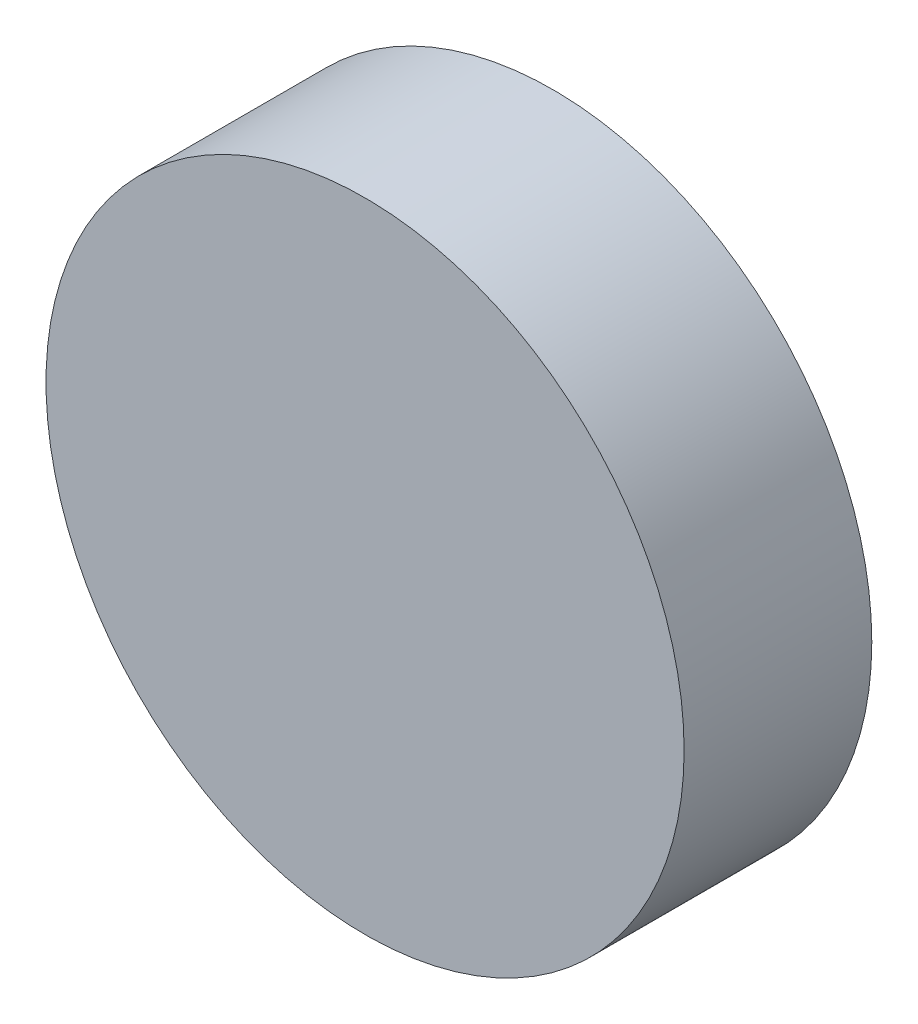
SolidWorks part; units mm, degrees
ref_plane "Front Plane" through (0, 0, 0) normal (0, 0, 1) x (1, 0, 0)
ref_plane "Top Plane" through (0, 0, 0) normal (0, 1, 0) x (1, 0, 0)
ref_plane "Right Plane" through (0, 0, 0) normal (1, 0, 0) x (0, 0, -1)
sketch "Sketch1" plane through (0, 0, 0) normal (0, 0, 1) x (1, 0, 0)
  circle A0 centre (40.506, 0.7624) radius 8.5
  dimension "D1" = 17
extrude "Boss-Extrude1" add sketch "Sketch1" along normal blind 5
